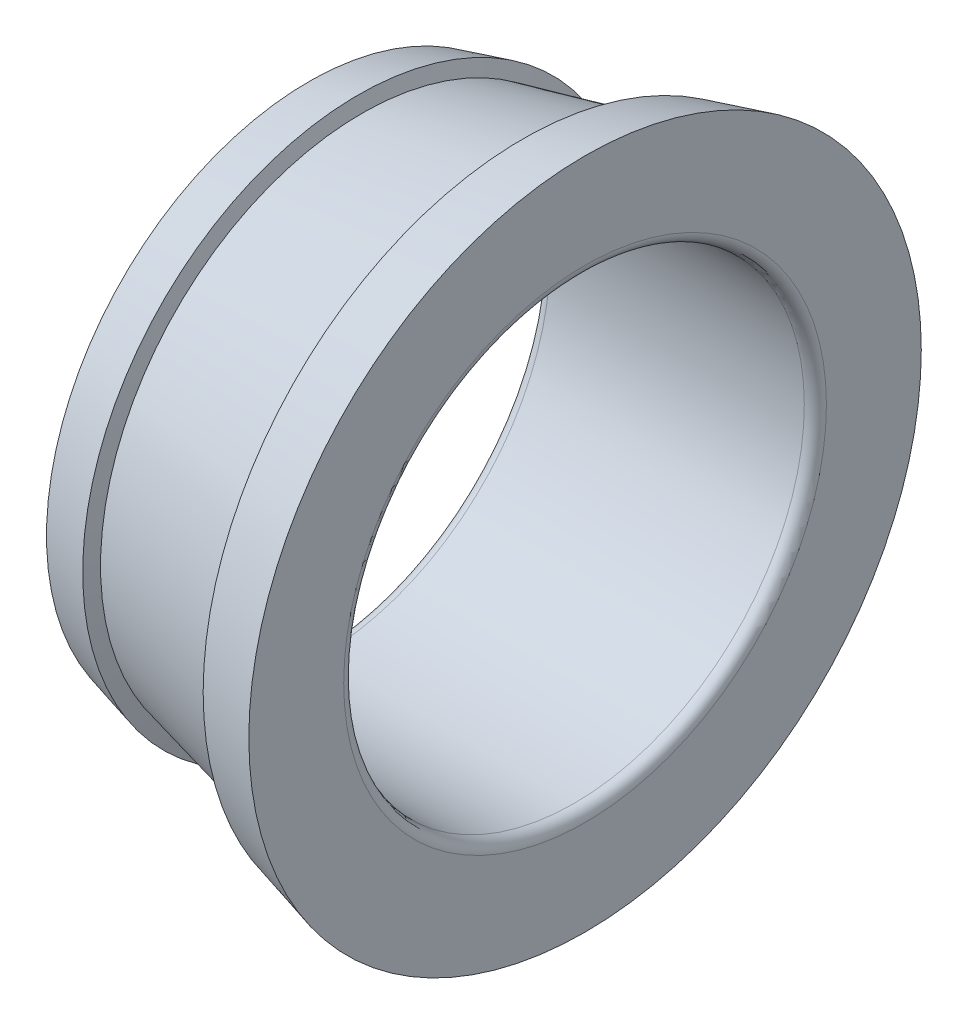
SolidWorks part; units mm, degrees
ref_plane "Plan1" through (0, 0, 0) normal (0, 0, 1) x (1, 0, 0)
ref_plane "Plan2" through (0, 0, 0) normal (0, 1, 0) x (1, 0, 0)
ref_plane "Plan3" through (0, 0, 0) normal (1, 0, 0) x (0, 0, -1)
sketch "Esquisse1" plane through (0, 0, 0) normal (0, 0, 1) x (1, 0, 0)
  line L0 (0, 0) -> (-85.618, 0) construction
  line L1 (0, 13.1) -> (0, 18.25)
  line L2 (-0.6, 12.5) -> (-14.4, 12.5)
  line L3 (-15, 13.1) -> (-15, 14.2308)
  line L4 (-15, 14.2308) -> (-12.3163, 14.9499)
  line L5 (-3.3856, 17.3428) -> (-3.108, 16.3067)
  line L6 (-12.3163, 14.9499) -> (-12.1118, 14.1866)
  line L7 (-3.108, 16.3067) -> (-12.1118, 14.1866)
  line L8 (-3.3856, 17.3428) -> (0, 18.25)
  arc A0 (0, 13.1) -> (-0.6, 12.5) centre (-0.6, 13.1) cw
  arc A1 (-14.4, 12.5) -> (-15, 13.1) centre (-14.4, 13.1) cw
  point P9 (0, 12.5)
  point P12 (-15, 12.5)
  point P15 (-68.1099, 0)
  dimension "D5" = 0.6
  dimension "D1" = 15
  dimension "D2" = 12.5
  dimension "D3" = 18.25
  dimension "D4" = 15
  dimension "D6" = 13.25
  dimension "D7" = 1.0727
  dimension "D8" = 3.3856
  dimension "D9" = 9.25
revolve "Base-Révolution" add sketch "Esquisse1" angle 360 about L0
